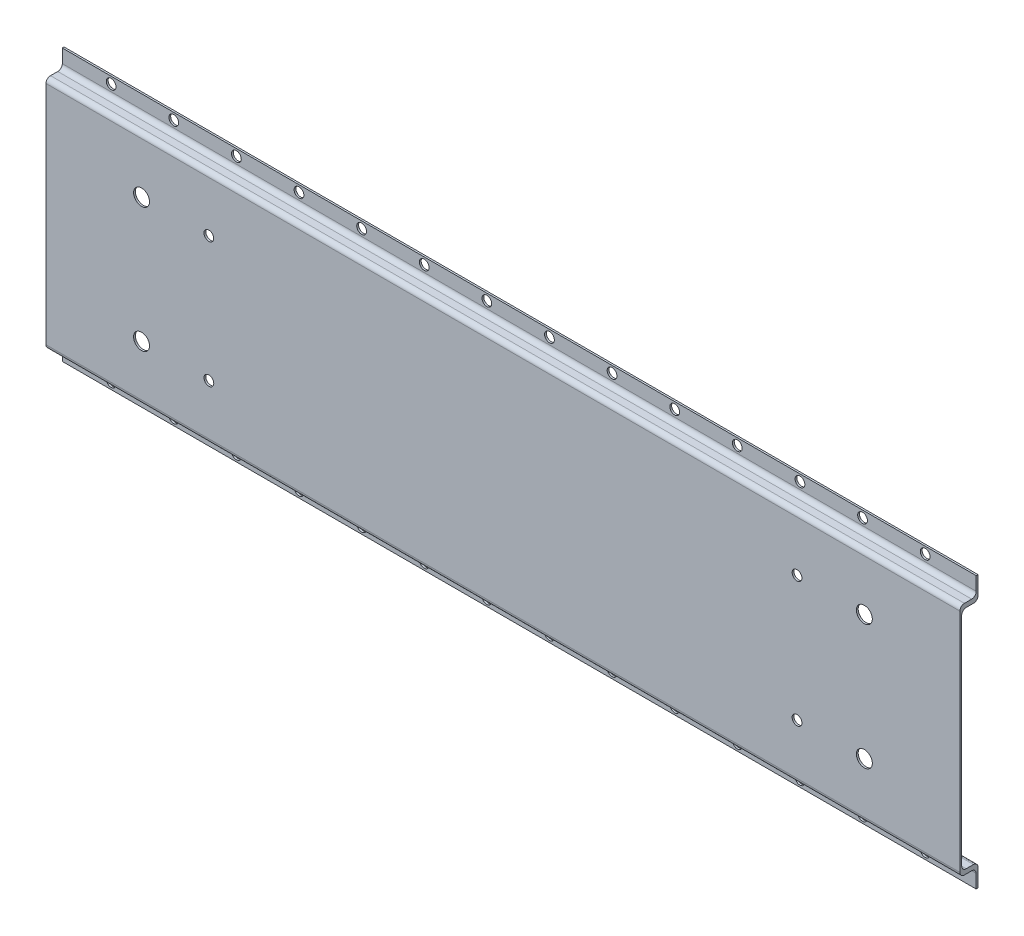
SolidWorks part; units mm, degrees
material "AISI 316 Stainless Steel Sheet (SS)"
ref_plane "Front Plane" through (0, 0, 0) normal (0, 0, 1) x (1, 0, 0)
ref_plane "Top Plane" through (0, 0, 0) normal (0, 1, 0) x (1, 0, 0)
ref_plane "Right Plane" through (0, 0, 0) normal (1, 0, 0) x (0, 0, -1)
sketch "Sketch1" plane through (0, 0, 0) normal (0, 0, 1) x (1, 0, 0)
  line L1 (-320.675, -95.25) -> (320.675, -95.25)
  line L2 (-320.675, -95.25) -> (-320.675, 95.25)
  line L3 (-320.675, 95.25) -> (320.675, 95.25)
  line L4 (320.675, -95.25) -> (320.675, 95.25)
  line L5 (-320.675, -95.25) -> (320.675, 95.25) construction
  line L6 (-320.675, 95.25) -> (320.675, -95.25) construction
  point P0 (0, 0)
  dimension "D1" = 641.35
  dimension "D2" = 190.5
extrude "Boss-Extrude1" add sketch "Sketch1" along normal blind 12.7
sketch "Sketch2" plane through (0, 0, 12.7) normal (0, 0, 1) x (1, 0, 0)
  line L0 (320.675, -95.25) -> (320.675, 95.25) construction
  line L1 (-320.675, 95.25) -> (320.675, 95.25)
  line L2 (-320.675, 95.25) -> (-320.675, 82.55)
  line L3 (-320.675, 82.55) -> (320.675, 82.55)
  line L4 (320.675, 95.25) -> (320.675, 82.55)
  line L6 (-320.675, -95.25) -> (320.675, -95.25)
  line L7 (-320.675, -95.25) -> (-320.675, -82.55)
  line L8 (-320.675, -82.55) -> (320.675, -82.55)
  line L9 (320.675, -95.25) -> (320.675, -82.55)
  dimension "D1" = 12.7
  dimension "D2" = 12.7
extrude "Cut-Extrude1" cut sketch "Sketch2" against normal blind 11.43 contours L2 L1 L4 L3 | L7 L6 L9 L8
sketch "Sketch4" plane through (0, 0, 0) normal (0, 0, -1) x (-1, 0, 0)
  line L0 (320.675, 95.25) -> (320.675, -95.25) construction
  line L1 (-320.675, -79.375) -> (320.675, -79.375)
  line L2 (-320.675, -79.375) -> (-320.675, 79.375)
  line L3 (-320.675, 79.375) -> (320.675, 79.375)
  line L4 (320.675, -79.375) -> (320.675, 79.375)
  line L5 (-320.675, -79.375) -> (320.675, 79.375) construction
  line L6 (-320.675, 79.375) -> (320.675, -79.375) construction
  point P0 (0, 0)
  dimension "D1" = 158.75
extrude "Cut-Extrude2" cut sketch "Sketch4" against normal blind 11.43 contours L2 L1 L4 L3
fillet "Fillet2" radius 3.175 8 edges at (0, -79.375, 11.43) (0, -82.55, 1.27) (0, -82.55, 12.7) (0, -79.375, 0) (0, 82.55, 1.27) (0, 82.55, 12.7) (0, 79.375, 11.43) (0, 79.375, 0)
sketch "Sketch6" plane through (0, 0, 1.27) normal (0, 0, 1) x (1, 0, 0)
  line L3 (-320.675, 0) -> (-242.443, 0)
  line L5 (-320.675, 79.375) -> (-320.675, -79.375) construction
  circle A0 centre (-286.385, 90.4875) radius 3.429
  circle A1 centre (-242.443, 90.4875) radius 3.429
  circle A2 centre (-198.501, 90.4875) radius 3.429
  circle A3 centre (-154.559, 90.4875) radius 3.429
  circle A4 centre (-110.617, 90.4875) radius 3.429
  circle A5 centre (-66.675, 90.4875) radius 3.429
  circle A6 centre (-22.733, 90.4875) radius 3.429
  circle A7 centre (21.209, 90.4875) radius 3.429
  circle A8 centre (65.151, 90.4875) radius 3.429
  circle A9 centre (109.093, 90.4875) radius 3.429
  circle A10 centre (153.035, 90.4875) radius 3.429
  circle A11 centre (196.977, 90.4875) radius 3.429
  circle A12 centre (240.919, 90.4875) radius 3.429
  circle A13 centre (284.861, 90.4875) radius 3.429
  circle A14 centre (284.861, -90.4875) radius 3.429
  circle A15 centre (240.919, -90.4875) radius 3.429
  circle A16 centre (196.977, -90.4875) radius 3.429
  circle A17 centre (153.035, -90.4875) radius 3.429
  circle A18 centre (109.093, -90.4875) radius 3.429
  circle A19 centre (65.151, -90.4875) radius 3.429
  circle A20 centre (21.209, -90.4875) radius 3.429
  circle A21 centre (-22.733, -90.4875) radius 3.429
  circle A22 centre (-66.675, -90.4875) radius 3.429
  circle A23 centre (-110.617, -90.4875) radius 3.429
  circle A24 centre (-154.559, -90.4875) radius 3.429
  circle A25 centre (-198.501, -90.4875) radius 3.429
  circle A26 centre (-242.443, -90.4875) radius 3.429
  circle A27 centre (-286.385, -90.4875) radius 3.429
  dimension "D2" = 6.858
  dimension "D1" = 14
extrude "Cut-Extrude3" cut sketch "Sketch6" against normal blind 11.43 contours A0 | A1 | A2 | A3 | A4 | A5 | A13 | A12 | A11 | A10 | A9 | A8 | A7 | A27 | A26 | A25 | A24 | A23 | A22 | A21 | A20 | A19 | A18 | A17 | A16 | A15 | A14 | A6
sketch "Sketch8" plane through (0, 0, 12.7) normal (0, 0, 1) x (1, 0, 0)
  line L0 (0, 0) -> (0, 40.2964)
  line L2 (0, 0) -> (43.1554, 0)
  circle A0 centre (-253.619, 43.815) radius 5.588
  circle A1 centre (253.619, 43.815) radius 5.588
  circle A2 centre (253.619, -43.815) radius 5.588
  circle A3 centre (-253.619, -43.815) radius 5.588
  dimension "D1" = 11.176
extrude "Cut-Extrude4" cut sketch "Sketch8" against normal blind 11.43 contours A0 | A3 | A1 | A2
sketch "Sketch9" plane through (0, 0, 12.7) normal (0, 0, 1) x (1, 0, 0)
  line L0 (0, 0) -> (32.6659, 0)
  line L2 (0, 0) -> (0, 30.4276)
  circle A0 centre (-206.375, 44.0153) radius 3.429
  circle A1 centre (206.375, 44.0153) radius 3.429
  circle A2 centre (206.375, -44.0153) radius 3.429
  circle A3 centre (-206.375, -44.0153) radius 3.429
  dimension "D2" = 6.858
extrude "Cut-Extrude5" cut sketch "Sketch9" against normal blind 11.43 contours A0 | A3 | A1 | A2
